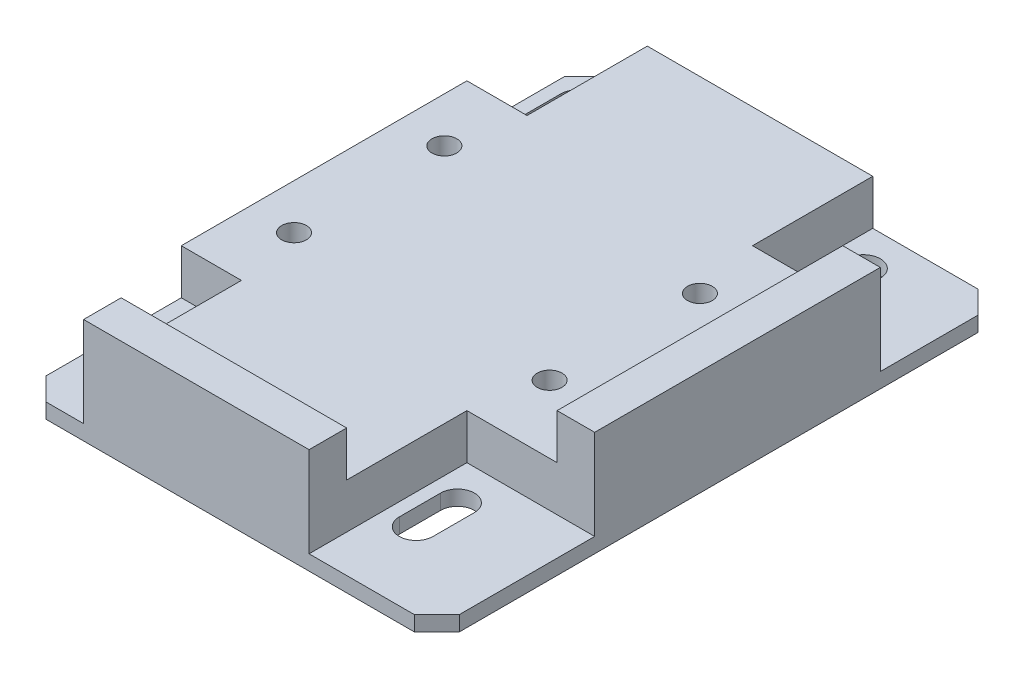
SolidWorks part; units mm, degrees
ref_plane "前视基准面" through (0, 0, 0) normal (0, 0, 1) x (1, 0, 0)
ref_plane "上视基准面" through (0, 0, 0) normal (0, 1, 0) x (1, 0, 0)
ref_plane "右视基准面" through (0, 0, 0) normal (1, 0, 0) x (0, 0, -1)
sketch "草图1" plane through (0, 0, 0) normal (0, 1, 0) x (1, 0, 0)
  line L1 (27.5, -37.5) -> (-27.5, -37.5)
  line L2 (27.5, -37.5) -> (27.5, 37.5)
  line L3 (27.5, 37.5) -> (-27.5, 37.5)
  line L4 (-27.5, -37.5) -> (-27.5, 37.5)
  line L5 (27.5, -37.5) -> (-27.5, 37.5) construction
  line L6 (27.5, 37.5) -> (-27.5, -37.5) construction
  point P0 (0, 0)
  dimension "D1" = 55
  dimension "D2" = 75
extrude "凸台-拉伸1" add sketch "草图1" along normal blind 14
sketch "草图2" plane through (0, 14, 0) normal (0, 1, 0) x (1, 0, 0)
  line L0 (27.5, -37.5) -> (27.5, 37.5) construction
  line L1 (-27.5, 37.5) -> (22.5, 37.5)
  line L2 (-27.5, 37.5) -> (-27.5, -32.5)
  line L3 (-27.5, -32.5) -> (22.5, -32.5)
  line L4 (22.5, 37.5) -> (22.5, -32.5)
  line L5 (-27.5, -37.5) -> (27.5, -37.5) construction
  point P8 (0, 0)
  dimension "D1" = 5
  dimension "D2" = 5
extrude "切除-拉伸1" cut sketch "草图2" against normal blind 6
sketch "草图3" plane through (0, 14, 0) normal (0, 1, 0) x (1, 0, 0)
  line L1 (27.5, -37.5) -> (10.5, -37.5)
  line L2 (27.5, -37.5) -> (27.5, -16.5)
  line L3 (27.5, -16.5) -> (10.5, -16.5)
  line L4 (10.5, -37.5) -> (10.5, -16.5)
  line L5 (27.5, 37.5) -> (10.5, 37.5)
  line L6 (27.5, 37.5) -> (27.5, 21.5)
  line L7 (27.5, 21.5) -> (10.5, 21.5)
  line L8 (10.5, 37.5) -> (10.5, 21.5)
  line L9 (-27.5, 37.5) -> (-19.5, 37.5)
  line L10 (-27.5, 37.5) -> (-27.5, 21.5)
  line L11 (-27.5, 21.5) -> (-19.5, 21.5)
  line L12 (-19.5, 37.5) -> (-19.5, 21.5)
  line L13 (-27.5, -37.5) -> (-19.5, -37.5)
  line L14 (-27.5, -37.5) -> (-27.5, -16.5)
  line L15 (-27.5, -16.5) -> (-19.5, -16.5)
  line L16 (-19.5, -37.5) -> (-19.5, -16.5)
  dimension "D1" = 17
  dimension "D2" = 21
  dimension "D3" = 17
  dimension "D4" = 16
  dimension "D5" = 8
  dimension "D6" = 16
  dimension "D7" = 8
  dimension "D8" = 21
extrude "切除-拉伸2" cut sketch "草图3" against normal blind 12
sketch "草图4" plane through (0, 2, 0) normal (0, 1, 0) x (1, 0, 0)
  line L0 (-23.5, 32.25) -> (-23.5, 26.75) construction
  line L1 (-21.25, 32.25) -> (-21.25, 26.75)
  line L2 (-25.75, 32.25) -> (-25.75, 26.75)
  line L3 (-27.5, 37.5) -> (-27.5, 21.5) construction
  line L4 (-19.5, 37.5) -> (-27.5, 37.5) construction
  line L5 (14.5, 32.25) -> (14.5, 26.75) construction
  line L6 (16.75, 32.25) -> (16.75, 26.75)
  line L7 (12.25, 32.25) -> (12.25, 26.75)
  line L8 (27.5, 37.5) -> (10.5, 37.5) construction
  line L9 (27.5, 21.5) -> (27.5, 37.5) construction
  line L10 (14.5, -21.75) -> (14.5, -27.25) construction
  line L11 (16.75, -21.75) -> (16.75, -27.25)
  line L12 (12.25, -21.75) -> (12.25, -27.25)
  line L13 (27.5, -37.5) -> (27.5, -16.5) construction
  line L14 (10.5, -37.5) -> (27.5, -37.5) construction
  line L15 (-23.5, -21.75) -> (-23.5, -27.25) construction
  line L16 (-21.25, -21.75) -> (-21.25, -27.25)
  line L17 (-25.75, -21.75) -> (-25.75, -27.25)
  line L18 (-27.5, -37.5) -> (-19.5, -37.5) construction
  arc A0 (-21.25, 32.25) -> (-25.75, 32.25) centre (-23.5, 32.25) ccw
  arc A1 (-25.75, 26.75) -> (-21.25, 26.75) centre (-23.5, 26.75) ccw
  arc A2 (16.75, 32.25) -> (12.25, 32.25) centre (14.5, 32.25) ccw
  arc A3 (12.25, 26.75) -> (16.75, 26.75) centre (14.5, 26.75) ccw
  arc A4 (16.75, -21.75) -> (12.25, -21.75) centre (14.5, -21.75) ccw
  arc A5 (12.25, -27.25) -> (16.75, -27.25) centre (14.5, -27.25) ccw
  arc A6 (-21.25, -21.75) -> (-25.75, -21.75) centre (-23.5, -21.75) ccw
  arc A7 (-25.75, -27.25) -> (-21.25, -27.25) centre (-23.5, -27.25) ccw
  point P2 (-23.5, 29.5)
  point P13 (14.5, 29.5)
  point P24 (14.5, -24.5)
  point P35 (-23.5, -24.5)
  dimension "D2" = 10
  dimension "D6" = 10
  dimension "D10" = 10
  dimension "D14" = 10
  dimension "D1" = 4.5
  dimension "D3" = 4
  dimension "D4" = 8
  dimension "D5" = 4.5
  dimension "D7" = 8
  dimension "D8" = 13
  dimension "D9" = 4.5
  dimension "D11" = 13
  dimension "D12" = 13
  dimension "D13" = 4.5
  dimension "D15" = 13
  dimension "D16" = 38
extrude "切除-拉伸3" cut sketch "草图4" against normal up to next
hole_wizard "M4 螺纹孔1" positions "草图6" profile "草图7" tap size "M4" standard "GB"
sketch "草图6" plane through (0, 8, 0) normal (0, 1, 0) x (1, 0, 0)
  line L0 (-19.5, -37.5) -> (10.5, -37.5) construction
  line L1 (27.5, -16.5) -> (27.5, 21.5) construction
  point P0 (-21.5, 12.5)
  dimension "D1" = 50
  dimension "D2" = 49
sketch "草图7" plane through (-21.5, 8, -12.5) normal (1, 0, 0) x (0, 0, 1)
  line L0 (0, 0) -> (0, 11.0914)
  line L1 (0, 11.0914) -> (1.65, 10.1)
  line L2 (1.65, 10.1) -> (1.65, 0)
  line L5 (1.65, 0) -> (0, 0)
  line L10 (0, 11.0914) -> (-1.65, 10.1) construction
  line L11 (0, -6.35) -> (0, 107.95) construction
  dimension "螺纹孔钻头直径" = 3.3
  dimension "螺纹孔钻头深度" = 10.1
  dimension "导头角度" = 118
cosmetic thread "孔螺蚊线1" parameters "D1"=8, "D2"=4
pattern_linear "阵列(线性)1" count 2 spacing 34 along (1, 0, 0) count 2 spacing 20 along (0, 0, 1) of "M4 螺纹孔1"
chamfer "倒角1" distance 3 angle 45 4 edges at (27.5, 1, 37.5) (27.5, 1, -37.5) (-27.5, 1, 37.5) (-27.5, 1, -37.5)
